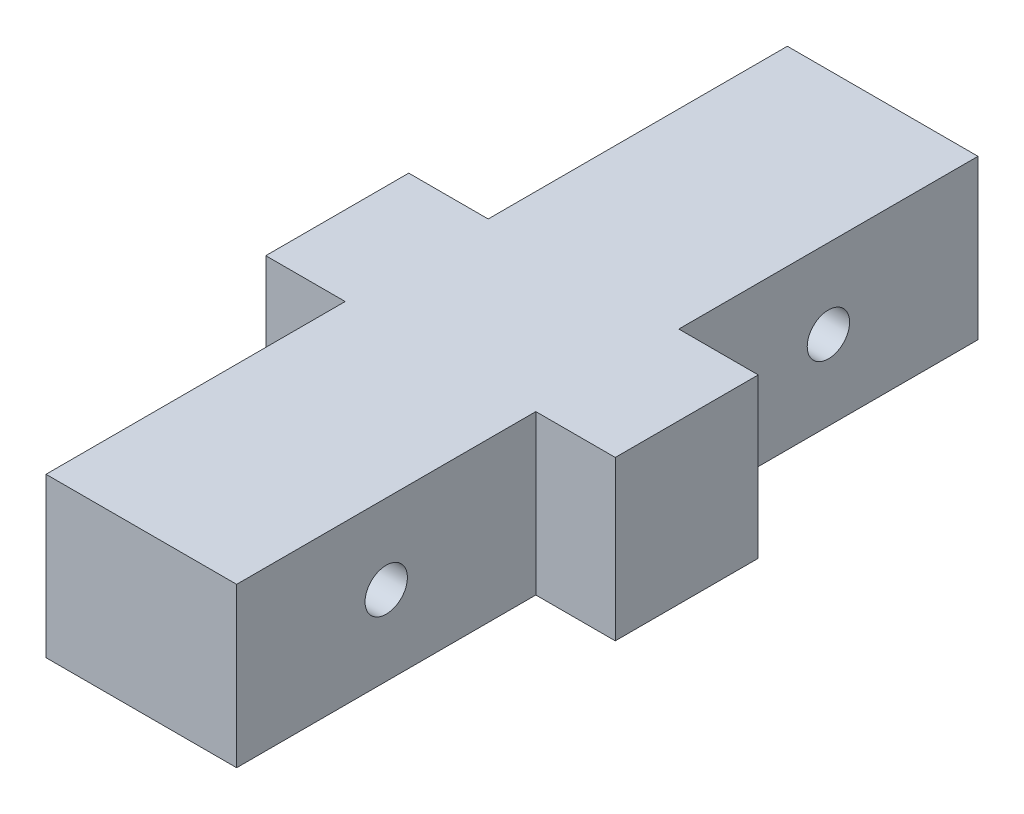
SolidWorks part; units mm, degrees
ref_plane "Front Plane" through (0, 0, 0) normal (0, 0, 1) x (1, 0, 0)
ref_plane "Top Plane" through (0, 0, 0) normal (0, 1, 0) x (1, 0, 0)
ref_plane "Right Plane" through (0, 0, 0) normal (1, 0, 0) x (0, 0, -1)
sketch "Sketch1" plane through (0, 0, 0) normal (0, 1, 0) x (1, 0, 0)
  line L0 (-66, 27) -> (-36, 27)
  line L1 (-66, 140) -> (66, 140) construction
  line L2 (-66, 140) -> (-66, -140) construction
  line L3 (-66, -140) -> (66, -140) construction
  line L4 (66, 140) -> (66, -140) construction
  line L5 (-66, 140) -> (66, -140) construction
  line L6 (-66, -140) -> (66, 140) construction
  line L7 (-36, 27) -> (-36, 140)
  line L8 (-36, 140) -> (36, 140)
  line L9 (36, 140) -> (36, 27)
  line L10 (36, 27) -> (66, 27)
  line L11 (66, 27) -> (66, -27)
  line L12 (66, -27) -> (36, -27)
  line L13 (36, -27) -> (36, -140)
  line L14 (36, -140) -> (-36, -140)
  line L15 (-36, -140) -> (-36, -27)
  line L16 (-36, -27) -> (-66, -27)
  line L17 (-66, 27) -> (-66, -27)
  point P0 (0, 0)
  dimension "D1" = 113
  dimension "D2" = 30
  dimension "D3" = 72
  dimension "D4" = 280
extrude "Boss-Extrude1" add sketch "Sketch1" along normal blind 60
sketch "Sketch2" plane through (-36, 0, 0) normal (-1, 0, 0) x (0, 0, 1)
  line L0 (140, 60) -> (27, 0) construction
  line L1 (-83.5, 30) -> (-75.5, 30) construction
  line L2 (27, 60) -> (140, 0) construction
  line L3 (-140, 60) -> (-27, 0) construction
  line L4 (83.5, 30) -> (75.5, 30) construction
  line L5 (-140, 60) -> (-27, 60) construction
  line L6 (-27, 60) -> (-27, 0) construction
  line L8 (-27, 60) -> (-140, 0) construction
  circle A0 centre (83.5, 30) radius 8
  circle A1 centre (-83.5, 30) radius 8
  dimension "D1" = 8
extrude "Cut-Extrude1" cut sketch "Sketch2" against normal through all both and the other way through all
sketch "Sketch3" plane through (36, 0, 0) normal (1, 0, 0) x (0, 0, -1)
  line L0 (-140, 0) -> (140, 0)
  line L1 (140, 0) -> (120.2972, -18.5356)
  line L2 (65.4808, -40.2677) -> (-65.4808, -40.2677)
  line L3 (-120.2972, -18.5356) -> (-140, 0)
  arc A0 (120.2972, -18.5356) -> (65.4808, -40.2677) centre (65.4808, 39.7323) cw
  arc A1 (-65.4808, -40.2677) -> (-120.2972, -18.5356) centre (-65.4808, 39.7323) cw
  dimension "D1" = 80
extrude "Boss-Extrude2" [suppressed] add sketch "Sketch3" against normal up to surface (72 mm away)
